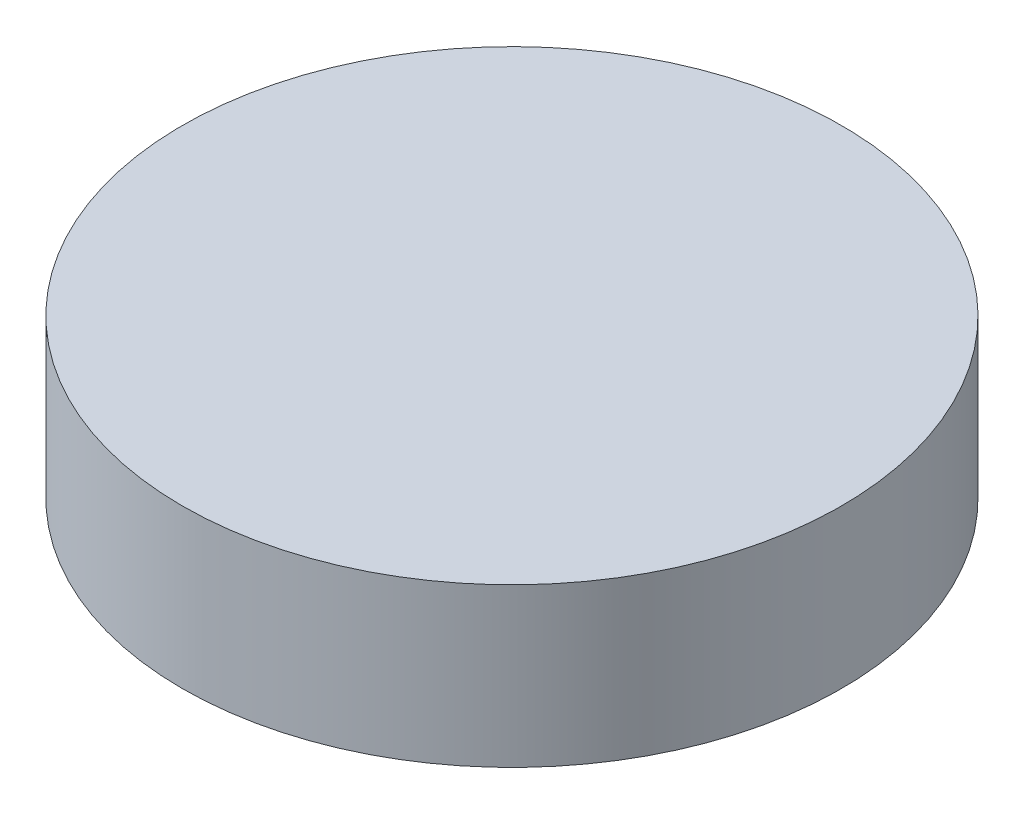
SolidWorks part; units mm, degrees
ref_plane "Front Plane" through (0, 0, 0) normal (0, 0, 1) x (1, 0, 0)
ref_plane "Top Plane" through (0, 0, 0) normal (0, 1, 0) x (1, 0, 0)
ref_plane "Right Plane" through (0, 0, 0) normal (1, 0, 0) x (0, 0, -1)
other "Configuration Table"
sketch "Sketch1" plane through (0, 0, 0) normal (0, 1, 0) x (1, 0, 0)
  circle A0 centre (650, 50) radius 25
extrude "OVEN_ayar_ayagi_2" add sketch "Sketch1" along normal blind 12 separate body
